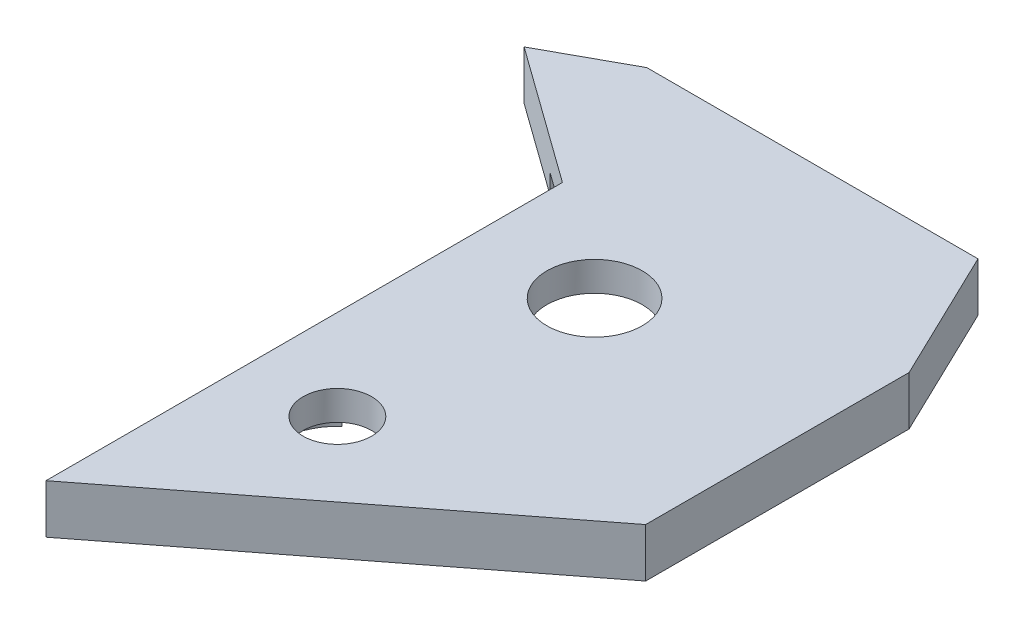
SolidWorks part; units mm, degrees
ref_plane "Спереди" through (0, 0, 0) normal (0, 0, 1) x (1, 0, 0)
ref_plane "Сверху" through (0, 0, 0) normal (0, 1, 0) x (1, 0, 0)
ref_plane "Справа" through (0, 0, 0) normal (1, 0, 0) x (0, 0, -1)
sketch "Эскиз1" plane through (0, 0, 0) normal (0, 1, 0) x (1, 0, 0)
  line L0 (0, 0) -> (8.097, 4.4371)
  line L1 (8.097, 4.4371) -> (41.9253, 4.4371)
  line L2 (41.9253, 4.4371) -> (48.4616, -9.1345)
  line L3 (48.4616, -9.1345) -> (48.4616, -36.0442)
  line L4 (48.4616, -36.0442) -> (13.951, -62.7883)
  line L5 (13.951, -62.7883) -> (13.9493, -10.034)
  line L6 (13.9493, -10.034) -> (0, 0)
extrude "Вытянуть1" add sketch "Эскиз1" along normal blind 5
sketch "Эскиз2" plane through (0, 0, 0) normal (0, -1, 0) x (1, 0, 0)
  arc A0 (19.2701, 37.8675) -> (27.9061, 38.8512) centre (25.8346, 18.6375) ccw
  arc A1 (27.9061, 38.8512) -> (19.2701, 37.8675) centre (23.1483, 42.2208) ccw
extrude "Вырез-Вытянуть1" cut sketch "Эскиз2" against normal blind 2
sketch "Эскиз3" plane through (0, 5, 0) normal (0, 1, 0) x (1, 0, 0)
  circle A0 centre (25.8346, -18.6375) radius 4.87
  circle A1 centre (23.1483, -42.2208) radius 3.5
extrude "Вырез-Вытянуть2" cut sketch "Эскиз3" against normal through all
